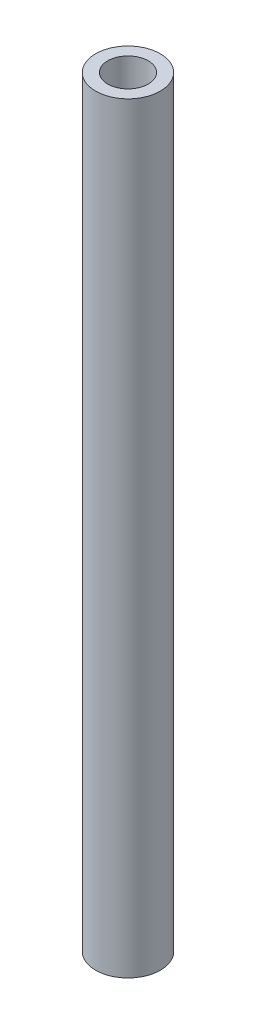
SolidWorks part; units mm, degrees
ref_plane "Płaszczyzna przednia" through (0, 0, 0) normal (0, 0, 1) x (1, 0, 0)
ref_plane "Płaszczyzna górna" through (0, 0, 0) normal (0, 1, 0) x (1, 0, 0)
ref_plane "Płaszczyzna prawa" through (0, 0, 0) normal (1, 0, 0) x (0, 0, -1)
sketch "Szkic1" plane through (0, 0, 0) normal (0, 1, 0) x (1, 0, 0)
  circle A0 centre (0, 0) radius 2.5
  circle A1 centre (0, 0) radius 4
  dimension "D1" = 5
  dimension "D2" = 8
extrude "Dodanie-wyciągnięcie1" add sketch "Szkic1" along normal blind 94.1
